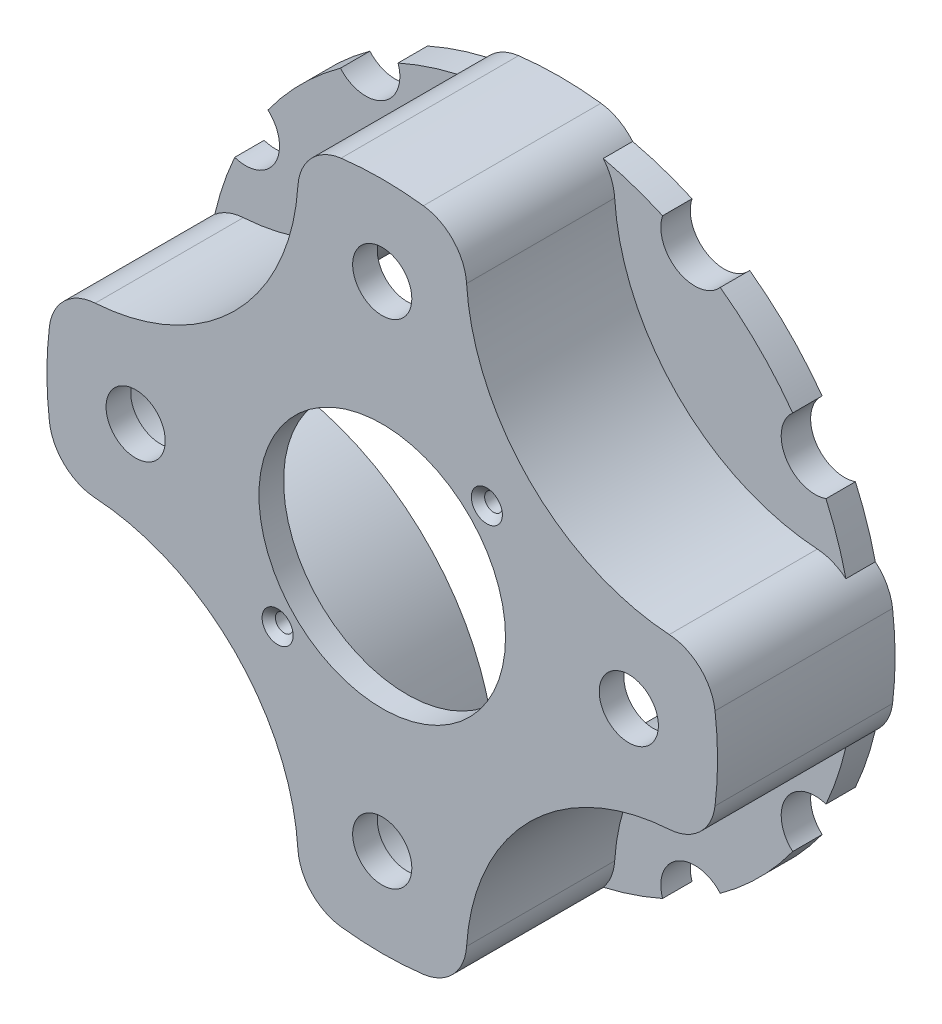
SolidWorks part; units mm, degrees
material "AISI 4340 Çelik, normalize"
ref_plane "Front" through (0, 0, 0) normal (0, 0, 1) x (1, 0, 0)
ref_plane "Top" through (0, 0, 0) normal (0, 1, 0) x (1, 0, 0)
ref_plane "Right" through (0, 0, 0) normal (1, 0, 0) x (0, 0, -1)
sketch "wheelhub sketch" plane through (0, 0, 0) normal (0, 0, 1) x (1, 0, 0)
  line L0 (-50, 0) -> (50, 0) construction
  line L1 (0, -50) -> (0, 50) construction
  circle A0 centre (0, 0) radius 62
  circle A1 centre (0, 50) radius 6
  circle A2 centre (-50, 0) radius 6
  circle A3 centre (0, -50) radius 6
  circle A4 centre (50, 0) radius 6
  circle A5 centre (-50, 0) radius 12
  circle A6 centre (0, 50) radius 12
  circle A7 centre (0, -50) radius 12
  circle A8 centre (50, 0) radius 12
  circle A9 centre (0, 0) radius 25
  arc A10 (-52.1317, 11.8091) -> (-11.8091, 52.1317) centre (-61.0139, 61.0139) ccw
  point P5 (0, 0)
  point P8 (0, 0)
  dimension "D1" = 124
  dimension "D4" = 12
  dimension "D5" = 50
  dimension "D6" = 50
  dimension "D2" = 100
  dimension "D3" = 100
sketch "Sketch6" plane through (0, 0, 0) normal (0, 0, 1) x (1, 0, 0)
  line L0 (-50, 0) -> (50, 0) construction
  circle A0 centre (0, 0) radius 68
  circle A1 centre (0, 0) radius 62
  circle A2 centre (0, 0) radius 64
  circle A3 centre (0, 0) radius 62 construction
  dimension "D1" = 136
  dimension "D2" = 2
  dimension "D3" = 4
  dimension "D4" = 128
extrude "Boss-Extrude1" add sketch "Sketch6" against normal blind 36 contours A0 A2 | A2 | A1
sketch "Sketch7" plane through (0, 0, 0) normal (0, 0, 1) x (1, 0, 0)
  line L0 (0, 0) -> (-61.0139, 61.0139) construction
  line L1 (0, -50) -> (0, 50) construction
  circle A1 centre (-61.0139, 61.0139) radius 44
  circle A5 centre (0, 50) radius 18
  circle A6 centre (-50, 0) radius 18
  circle A8 centre (-50, 0) radius 12 construction
  dimension "D1" = 45
  dimension "D2" = 6
extrude "Cut-Extrude2" cut sketch "Sketch7" against normal offset from surface (30.031 mm away) 5.969 from surface at 0 up to face at (68, 0, -36) starting at face at (68, 0, 0)
pattern_circular "CirPattern1" count 4 over 360 about axis through (0, 0, 0) along (0, 0, 1) of "Cut-Extrude2"
sketch "Sketch9" plane through (0, 0, -36) normal (0, 0, -1) x (-1, 0, 0)
  arc A16 (17.2717, 65.77) -> (-17.2717, 65.77) centre (0, 0) ccw construction
  arc A17 (13.042, 62.657) -> (62.657, 13.042) centre (61.0139, 61.0139) ccw
  arc A19 (-65.77, 17.2717) -> (-17.2717, 65.77) centre (-61.0139, 61.0139) ccw construction
  arc A20 (-65.77, 17.2717) -> (-65.77, -17.2717) centre (0, 0) ccw construction
  arc A21 (-17.2717, -65.77) -> (-65.77, -17.2717) centre (-61.0139, -61.0139) ccw construction
  arc A22 (-17.2717, -65.77) -> (17.2717, -65.77) centre (0, 0) ccw construction
  arc A23 (65.77, -17.2717) -> (17.2717, -65.77) centre (61.0139, -61.0139) ccw construction
  arc A24 (65.77, -17.2717) -> (65.77, 17.2717) centre (0, 0) ccw construction
  arc A26 (17.2717, 65.77) -> (65.77, 17.2717) centre (61.0139, 61.0139) ccw construction
  arc A28 (13.042, 62.657) -> (62.657, 13.042) centre (61.0139, 61.0139) ccw
  arc A30 (62.657, -13.042) -> (13.042, -62.657) centre (61.0139, -61.0139) ccw
  arc A32 (62.657, -13.042) -> (13.042, -62.657) centre (61.0139, -61.0139) ccw
  arc A33 (-13.042, -62.657) -> (-62.657, -13.042) centre (-61.0139, -61.0139) ccw
  arc A34 (-13.042, -62.657) -> (-62.657, -13.042) centre (-61.0139, -61.0139) ccw
  arc A35 (-62.657, 13.042) -> (-13.042, 62.657) centre (-61.0139, 61.0139) ccw
  arc A36 (-62.657, 13.042) -> (-13.042, 62.657) centre (-61.0139, 61.0139) ccw
  arc A37 (-13.042, -62.657) -> (13.042, -62.657) centre (0, 0) ccw
  arc A38 (-13.042, -62.657) -> (13.042, -62.657) centre (0, 0) ccw
  arc A39 (-62.657, 13.042) -> (-62.657, -13.042) centre (0, 0) ccw
  arc A40 (-62.657, 13.042) -> (-62.657, -13.042) centre (0, 0) ccw
  arc A41 (13.042, 62.657) -> (-13.042, 62.657) centre (0, 0) ccw
  arc A42 (13.042, 62.657) -> (-13.042, 62.657) centre (0, 0) ccw
  arc A43 (62.657, -13.042) -> (62.657, 13.042) centre (0, 0) ccw
  arc A44 (62.657, -13.042) -> (62.657, 13.042) centre (0, 0) ccw
  arc A45 (17.2717, 65.77) -> (-17.2717, 65.77) centre (0, 0) ccw
  arc A46 (-65.77, 17.2717) -> (-17.2717, 65.77) centre (-61.0139, 61.0139) ccw
  arc A47 (-65.77, 17.2717) -> (-65.77, -17.2717) centre (0, 0) ccw
  arc A64 (-17.2717, -65.77) -> (-65.77, -17.2717) centre (-61.0139, -61.0139) ccw
  arc A65 (-17.2717, -65.77) -> (17.2717, -65.77) centre (0, 0) ccw
  arc A66 (65.77, -17.2717) -> (17.2717, -65.77) centre (61.0139, -61.0139) ccw
  arc A67 (65.77, -17.2717) -> (65.77, 17.2717) centre (0, 0) ccw
  arc A68 (17.2717, 65.77) -> (65.77, 17.2717) centre (61.0139, 61.0139) ccw
  dimension "D1" = 4
extrude "Cut-Extrude3" cut sketch "Sketch9" against normal offset from surface (31 mm away) 5 contours A32 A44 A28 A42 A36 A40 A34 A38 up to face at (0, 0, 0)
fillet "Fillet4" radius 10 16 edges at (-65.77, 17.2717, -15.0155) (-17.2717, 65.77, -15.0155) (17.2717, 65.77, -15.0155) (65.77, 17.2717, -15.0155) (65.77, -17.2717, -15.0155) (17.2717, -65.77, -15.0155) (-17.2717, -65.77, -15.0155) (-65.77, -17.2717, -15.0155) (62.657, -13.042, -20.5) (62.657, 13.042, -20.5) (13.042, -62.657, -20.5) (-13.042, -62.657, -20.5) (-62.657, -13.042, -20.5) (-62.657, 13.042, -20.5) (-13.042, 62.657, -20.5) (13.042, 62.657, -20.5)
sketch "Sketch10" plane through (0, 0, -30.031) normal (0, 0, 1) x (1, 0, 0)
  line L0 (0, 0) -> (0, 66.675) construction
  line L1 (0, 0) -> (-33.3375, 57.7422) construction
  line L2 (0, 0) -> (-90.3596, 0) construction
  line L3 (0, 0) -> (-57.7422, 33.3375) construction
  circle A0 centre (0, 0) radius 65.675
  circle A2 centre (-33.3375, 57.7422) radius 6.88
  circle A3 centre (0, 0) radius 68 construction
  circle A4 centre (0, 0) radius 68
  circle A5 centre (0, 0) radius 66.675 construction
  circle A6 centre (-57.7422, 33.3375) radius 6.88
  arc M4 (-17.1039, 58.2002) -> (-8.3528, 67.485) centre (-7.1244, 57.5608) cw
  arc M5 (-8.3528, 67.485) -> (-67.485, 8.3528) centre (0, 0) ccw
  arc M6 (-67.485, 8.3528) -> (-58.2002, 17.1039) centre (-57.5608, 7.1244) cw
  dimension "D2" = 13.76
  dimension "D3" = 66.675
  dimension "D4" = 30
  dimension "D6" = 1
  dimension "D1" = 30
  dimension "D5" = 30
extrude "Cut-Extrude5" cut sketch "Sketch10" against normal through all contours A5 A6 A4 | A6 A5 M5 M6 | A6 A5 A2 M5 | A5 A2 M5 | A5 A2 M4 M5 | A2 A5 | A5 A6
pattern_circular "CirPattern3" count 4 over 360 about axis through (0, 0, 0) along (0, 0, 1) of "Cut-Extrude5"
sketch "Sketch11" plane through (0, 0, 0) normal (0, 0, 1) x (1, 0, 0)
  circle A0 centre (0, -50) radius 6 construction
  circle A1 centre (50, 0) radius 6 construction
  circle A2 centre (0, 50) radius 6 construction
  circle A3 centre (0, 0) radius 25 construction
  circle A4 centre (-50, 0) radius 6 construction
  circle A5 centre (0, -50) radius 6
  circle A6 centre (50, 0) radius 6
  circle A7 centre (0, 50) radius 6
  circle A8 centre (0, 0) radius 25
  circle A9 centre (-50, 0) radius 6
extrude "Cut-Extrude6" cut sketch "Sketch11" against normal through all
sketch "Sketch12" plane through (0, 0, 0) normal (0, 0, 1) x (1, 0, 0)
  line L0 (21.2132, 21.2132) -> (-21.2132, -21.2132)
  line L1 (0, 0) -> (0, -30.5359) construction
  circle A0 centre (21.2132, 21.2132) radius 1.5
  circle A1 centre (-21.2132, -21.2132) radius 1.5
  point P4 (0, 0)
  dimension "D3" = 3
  dimension "D1" = 45
  dimension "D2" = 60
extrude "Cut-Extrude7" cut sketch "Sketch12" against normal through all
hole_wizard "CSK for M3 Flat Head Machine Screw1" positions "Sketch13" profile "Sketch14" countersink size "M3" standard "ANSI Metric"
sketch "Sketch13" plane through (0, 0, 0) normal (0, 0, 1) x (1, 0, 0)
  point P0 (21.2132, 21.2132)
  point P3 (-21.2132, -21.2132)
sketch "Sketch14" plane through (21.2132, 21.2132, 0) normal (1, 0, 0) x (0, -1, 0)
  line L0 (0, 0) -> (0, 11.0815)
  line L1 (0, 11.0815) -> (1.8, 10)
  line L2 (1.8, 10) -> (1.8, 1.35)
  line L3 (1.8, 1.35) -> (3.15, 0)
  line L5 (3.15, 0) -> (0, 0)
  line L6 (-1.8, 1.35) -> (-3.15, 0) construction
  line L10 (0, 11.0815) -> (-1.8, 10) construction
  line L11 (0, -6.35) -> (0, 107.95) construction
  dimension "Hole Dia." = 3.6
  dimension "Hole Depth" = 10
  dimension "Near C'Sink Dia." = 6.3
  dimension "Near C'Sink Angle" = 90
  dimension "Drill Angle" = 118
